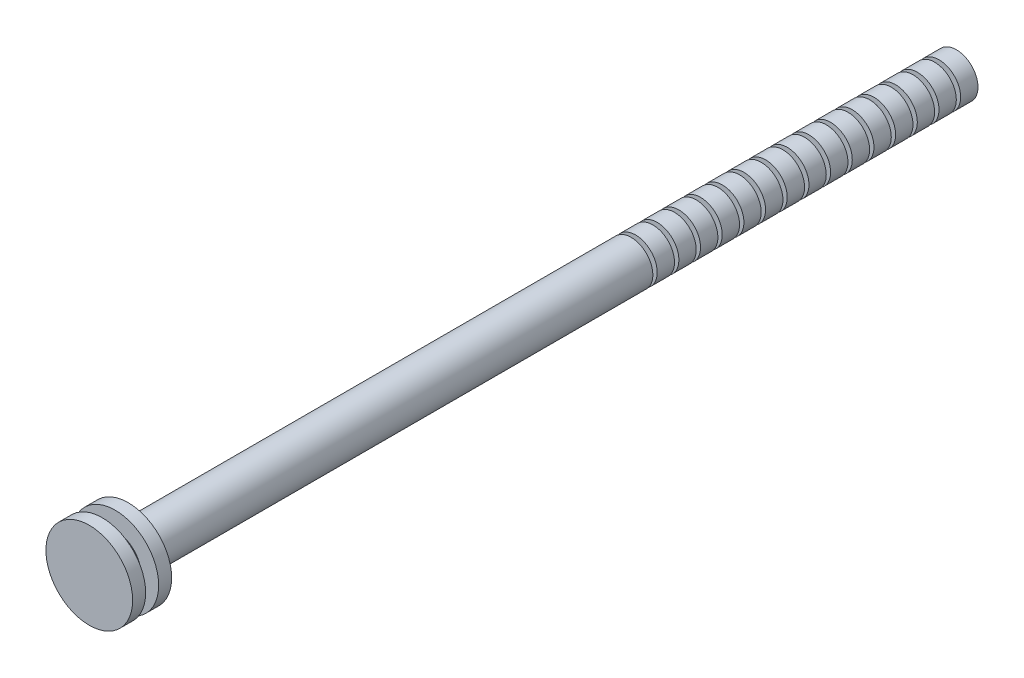
SolidWorks part; units mm, degrees
ref_plane "Front Plane" through (0, 0, 0) normal (0, 0, 1) x (1, 0, 0)
ref_plane "Top Plane" through (0, 0, 0) normal (0, 1, 0) x (1, 0, 0)
ref_plane "Right Plane" through (0, 0, 0) normal (1, 0, 0) x (0, 0, -1)
sketch "Sketch2" plane through (0, 0, 0) normal (0, 1, 0) x (1, 0, 0)
  line L0 (0, 0) -> (10, 0)
  line L1 (10, 0) -> (10, 3)
  line L2 (10, 3) -> (6, 3)
  line L3 (6, 3) -> (6, 6)
  line L4 (6, 6) -> (10, 6)
  line L5 (10, 6) -> (10, 9)
  line L6 (10, 9) -> (5, 9)
  line L7 (5, 9) -> (5, 200)
  line L8 (0, 0) -> (0, 200)
  line L9 (0, 200) -> (5, 200)
  dimension "D1" = 5
  dimension "D2" = 10
  dimension "D3" = 3
  dimension "D4" = 3
  dimension "D5" = 3
  dimension "D6" = 200
  dimension "D7" = 1
ref_axis "Axis1" through (0, 0, 0) along (0, 0, -1)
revolve "Revolve1" add sketch "Sketch2" angle 360 about L8
sketch "Sketch3" plane through (0, 0, 0) normal (0, 1, 0) x (1, 0, 0)
  line L0 (5, 196) -> (3, 196)
  line L1 (5, 9) -> (5, 200) construction
  line L2 (3, 196) -> (3, 195)
  line L3 (3, 195) -> (5, 195)
  line L4 (5, 195) -> (5, 196)
  line L5 (5, 200) -> (-5, 200) construction
  dimension "D1" = 2
  dimension "D2" = 1
  dimension "D3" = 4
revolve "Cut-Revolve1" cut sketch "Sketch3" angle 360 about axis through (0, 0, 0) along (0, 0, -1)
pattern_linear "LPattern1" count 15 spacing 5 along (0, 0, 1) of "Cut-Revolve1"
